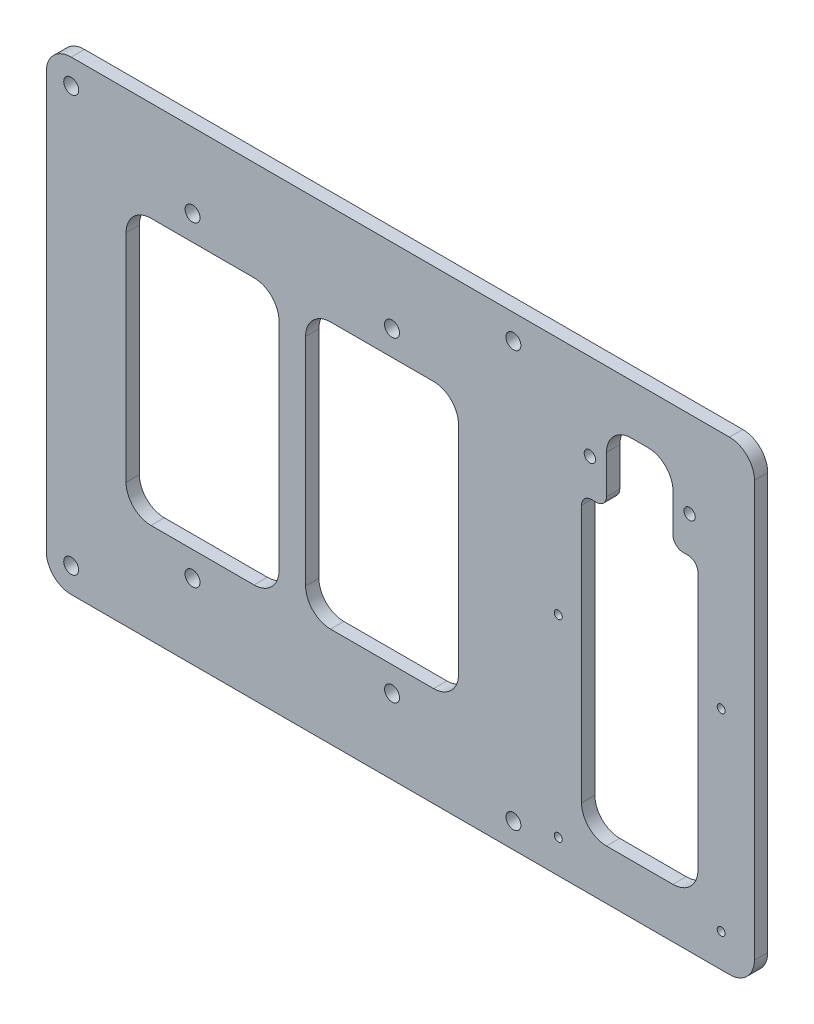
SolidWorks part; units mm, degrees
material "MDF"
ref_plane "正面" through (0, 0, 0) normal (1, 0, 0) x (0, 1, 0)
ref_plane "平面" through (0, 0, 0) normal (0, 0, 1) x (0, 1, 0)
ref_plane "右側面" through (0, 0, 0) normal (0, 1, 0) x (-1, 0, 0)
sketch "ｽｹｯﾁ1" plane through (0, 0, 0) normal (0, 0, 1) x (0, 1, 0)
  line L0 (30, -70) -> (110, -70)
  line L1 (0, 0) -> (140, 0)
  line L2 (0, 0) -> (0, -148)
  line L3 (0, -148) -> (140, -148)
  line L4 (140, 0) -> (140, -148)
  line L5 (70, -148) -> (70, 0) construction
  line L6 (0, -74) -> (140, -74) construction
  line L7 (110, -124) -> (30, -124)
  line L8 (110, -124) -> (110, -78)
  line L9 (110, -24) -> (30, -24)
  line L10 (30, -124) -> (30, -78)
  line L11 (110, -124) -> (30, -24) construction
  line L12 (110, -24) -> (30, -124) construction
  line L14 (110, -78) -> (30, -78)
  line L15 (30, -70) -> (30, -24)
  line L16 (110, -70) -> (110, -24)
  point P4 (70, -74)
  point P13 (0, 0)
  point P512 (70, -74)
  dimension "D1" = 148
  dimension "D2" = 140
  dimension "D3" = 80
  dimension "D4" = 100
  dimension "D5" = 4
  dimension "D6" = 4
extrude "ﾎﾞｽ - 押し出し1" add sketch "ｽｹｯﾁ1" along normal blind 4
sketch "ｽｹｯﾁ2" plane through (0, 0, 4) normal (0, 0, 1) x (1, 0, 0)
  line L0 (0, 0) -> (148, 0) construction
  line L1 (148, 140) -> (0, 140) construction
  point P0 (7.5, 132.5)
  point P1 (140.5, 132.5)
  point P2 (7.5, 7.5)
  point P3 (140.5, 7.5)
  point P10 (74, 140)
  dimension "D1" = 7.5
  dimension "D2" = 7.5
  dimension "D3" = 133
  dimension "D5" = 66.5
hole_wizard "M4 すきま穴1" positions "ｽｹｯﾁ2" profile "ｽｹｯﾁ3" hole size "M4" standard "JIS" end condition through all
sketch "ｽｹｯﾁ3" plane through (7.5, 132.5, 4) normal (1, 0, 0) x (0, -1, 0)
  line L0 (0, 0) -> (0, 4)
  line L1 (0, 4) -> (2.25, 4)
  line L2 (2.25, 4) -> (2.25, 0)
  line L5 (2.25, 0) -> (0, 0)
  line L11 (0, -6.35) -> (0, 107.95) construction
  dimension "通し穴の直径" = 4.5
  dimension "通し穴の深さ" = 4
sketch "ｽｹｯﾁ4" plane through (0, 0, 4) normal (0, 0, 1) x (1, 0, 0)
  line L0 (148, 140) -> (0, 140) construction
  line L1 (148, 0) -> (148, 140) construction
  line L2 (148, 70) -> (0, 70) construction
  line L3 (0, 140) -> (0, 0) construction
  point P0 (44, 117.5)
  point P1 (104, 117.5)
  point P4 (74, 140)
  point P7 (148, 70)
  point P8 (104, 22.5)
  point P13 (44, 22.5)
  dimension "D1" = 60
  dimension "D2" = 30
  dimension "D3" = 47.5
hole_wizard "Ø4.5 (4.5) 直径の穴1" positions "ｽｹｯﾁ4" profile "ｽｹｯﾁ5" hole size "Ø4.5" standard "JIS" end condition through all
sketch "ｽｹｯﾁ5" plane through (44, 117.5, 4) normal (1, 0, 0) x (0, -1, 0)
  line L0 (0, 0) -> (0, 4)
  line L1 (0, 4) -> (2.25, 4)
  line L2 (2.25, 4) -> (2.25, 0)
  line L5 (2.25, 0) -> (0, 0)
  line L11 (0, -6.35) -> (0, 107.95) construction
  dimension "通し穴の直径" = 4.5
  dimension "通し穴の深さ" = 4
sketch "ｽｹｯﾁ9" plane through (0, 0, 4) normal (0, 0, 1) x (1, 0, 0)
  line L0 (148, 140) -> (0, 140) construction
  line L7 (148, 0) -> (213, 0)
  line L8 (148, 0) -> (148, 140)
  line L9 (148, 140) -> (213, 140)
  line L10 (213, 0) -> (213, 140)
  line L11 (148, 0) -> (213, 140) construction
  line L12 (148, 140) -> (213, 0) construction
  point P10 (180.5, 70)
  dimension "D3" = 65
extrude "ﾎﾞｽ - 押し出し3" add sketch "ｽｹｯﾁ9" against normal blind 4
sketch "ｽｹｯﾁ11" plane through (0, 0, 4) normal (0, 0, 1) x (1, 0, 0)
  line L0 (213, 0) -> (213, 140) construction
  line L1 (0, 0) -> (213, 0) construction
  point P0 (203, 10)
  point P1 (154, 68)
  point P7 (203, 68)
  point P9 (154, 10)
  point P10 (0, 0)
  point P11 (0, 0)
  point P12 (0, 0)
  point P13 (0, 0)
  dimension "D1" = 49
  dimension "D2" = 58
  dimension "D3" = 10
  dimension "D4" = 10
hole_wizard "M2 すきま穴1" positions "ｽｹｯﾁ11" profile "ｽｹｯﾁ12" hole size "M2" standard "JIS" end condition through all
sketch "ｽｹｯﾁ12" plane through (203, 10, 4) normal (1, 0, 0) x (0, -1, 0)
  line L0 (0, 0) -> (0, 4)
  line L1 (0, 4) -> (1.2, 4)
  line L2 (1.2, 4) -> (1.2, 0)
  line L5 (1.2, 0) -> (0, 0)
  line L11 (0, -6.35) -> (0, 107.95) construction
  dimension "通し穴の直径" = 2.4
  dimension "通し穴の深さ" = 4
sketch "ｽｹｯﾁ13" plane through (0, 0, 4) normal (0, 0, 1) x (1, 0, 0)
  line L0 (0, 0) -> (213, 0) construction
  line L1 (168.5, 125) -> (188.5, 125)
  line L2 (168.5, 125) -> (168.5, 103)
  line L4 (188.5, 125) -> (188.5, 103)
  line L5 (168.5, 125) -> (188.5, 103) construction
  line L6 (168.5, 103) -> (188.5, 125) construction
  line L7 (154, 68) -> (203, 68) construction
  line L8 (154, 68) -> (154, 10) construction
  line L9 (154, 10) -> (203, 10) construction
  line L10 (203, 68) -> (203, 10) construction
  line L11 (161, 103) -> (168.5, 103)
  line L12 (161, 103) -> (161, 15)
  line L13 (161, 15) -> (196, 15)
  line L14 (196, 103) -> (196, 15)
  line L15 (213, 140) -> (0, 140) construction
  line L16 (188.5, 103) -> (196, 103)
  point P4 (178.5, 114)
  point P11 (178.5, 68)
  point P20 (0, 0)
  point P21 (178.5, 15)
  point P22 (192.25, 103)
  dimension "D1" = 20
  dimension "D2" = 15
  dimension "D3" = 35
  dimension "D4" = 15
  dimension "D5" = 35
extrude "ｶｯﾄ - 押し出し1" cut sketch "ｽｹｯﾁ13" against normal through all
sketch "ｽｹｯﾁ14" plane through (0, 0, 4) normal (0, 0, 1) x (1, 0, 0)
  line L0 (168.5, 125) -> (168.5, 103) construction
  line L1 (188.5, 103) -> (188.5, 125) construction
  point P0 (163.5, 114)
  point P1 (193.5, 114)
  point P6 (168.5, 114)
  dimension "D1" = 5
  dimension "D2" = 5
hole_wizard "M3 すきま穴1" positions "ｽｹｯﾁ14" profile "ｽｹｯﾁ15" hole size "M3" standard "JIS" end condition through all
sketch "ｽｹｯﾁ15" plane through (163.5, 114, 4) normal (1, 0, 0) x (0, -1, 0)
  line L0 (0, 0) -> (0, 4)
  line L1 (0, 4) -> (1.7, 4)
  line L2 (1.7, 4) -> (1.7, 0)
  line L5 (1.7, 0) -> (0, 0)
  line L11 (0, -6.35) -> (0, 107.95) construction
  dimension "通し穴の直径" = 3.4
  dimension "通し穴の深さ" = 4
fillet "ﾌｨﾚｯﾄ6" radius 7.5 16 edges at (124, 30, 2) (124, 110, 2) (0, 140, 2) (0, 0, 2) (78, 110, 2) (78, 30, 2) (70, 30, 2) (70, 110, 2) (24, 110, 2) (24, 30, 2) (213, 0, 2) (213, 140, 2) (168.5, 125, 2) (188.5, 125, 2) (196, 15, 2) (161, 15, 2)
fillet "ﾌｨﾚｯﾄ8" radius 3 4 edges at (188.5, 103, 2) (161, 103, 2) (168.5, 103, 2) (196, 103, 2)
equation "\"D1@ｽｹｯﾁ2\"= \"D2@ｽｹｯﾁ2\""
equation "\"D5@ｽｹｯﾁ2\"= \"D3@ｽｹｯﾁ2\" / 2"
